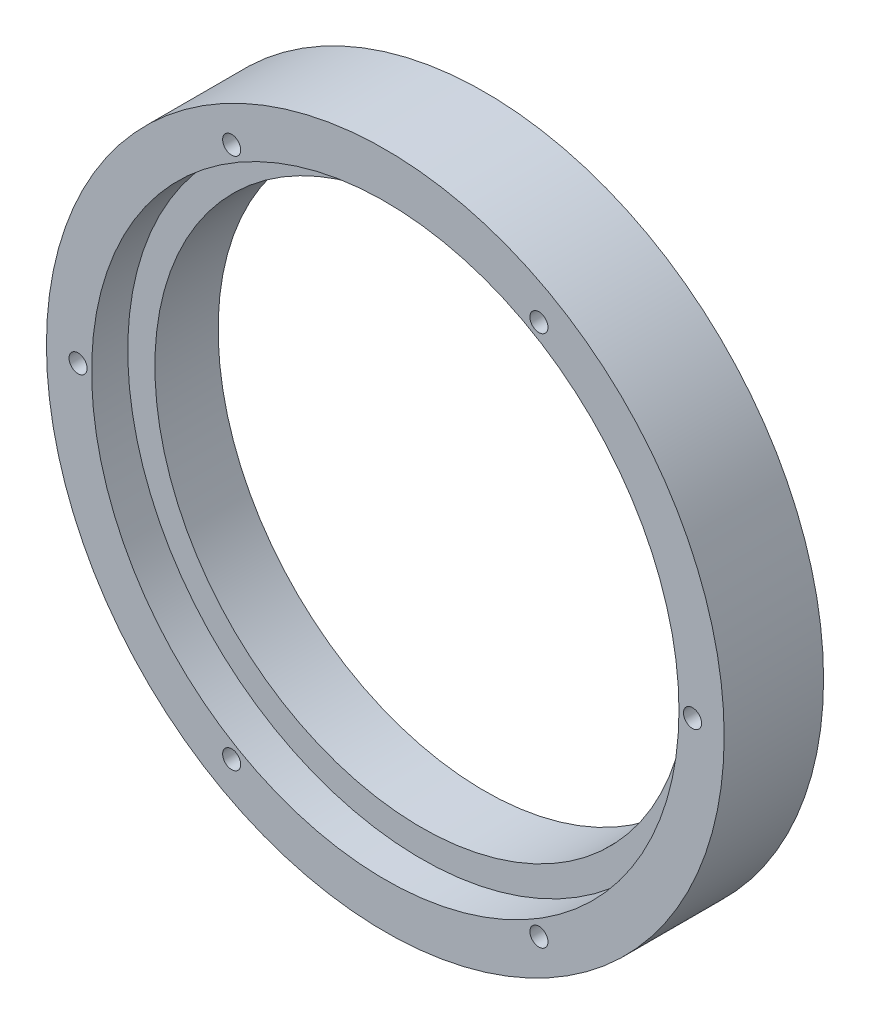
SolidWorks part; units mm, degrees
material "ABS"
ref_plane "Front Plane" through (0, 0, 0) normal (0, 0, 1) x (1, 0, 0)
ref_plane "Top Plane" through (0, 0, 0) normal (0, 1, 0) x (1, 0, 0)
ref_plane "Right Plane" through (0, 0, 0) normal (1, 0, 0) x (0, 0, -1)
sketch "Sketch1" plane through (0, 0, 0) normal (0, 0, 1) x (1, 0, 0)
  circle A0 centre (0, 0) radius 37.5
  circle A1 centre (0, 0) radius 29.5
extrude "Boss-Extrude1" add sketch "Sketch1" along normal blind 11
sketch "Sketch2" plane through (0, 0, 0) normal (0, 0, -1) x (-1, 0, 0)
  line L0 (-73.7646, 0) -> (58.2851, 0) construction
  line L1 (27.966, 48.4385) -> (0, 0) construction
  line L2 (0, 0) -> (-33.8549, -58.6384) construction
  line L3 (0, 0) -> (-31.6308, 54.7862) construction
  line L4 (-31.6308, 54.7862) -> (37.1164, -64.2875) construction
  circle A0 centre (0, 0) radius 34 construction
  circle A1 centre (-17, 29.4449) radius 1
  circle A2 centre (0, 0) radius 32.5 construction
  circle A3 centre (17, 29.4449) radius 1
  circle A4 centre (34, 0) radius 1
  circle A5 centre (17, -29.4449) radius 1
  circle A6 centre (-17, -29.4449) radius 1
  circle A7 centre (-34, 0) radius 1
  dimension "D1" = 60
  dimension "D2" = 60
extrude "Cut-Extrude1" cut sketch "Sketch2" against normal blind 11
sketch "Sketch3" plane through (0, 0, 11) normal (0, 0, 1) x (1, 0, 0)
  circle A0 centre (0, 0) radius 32.5
extrude "Cut-Extrude2" cut sketch "Sketch3" against normal blind 4
